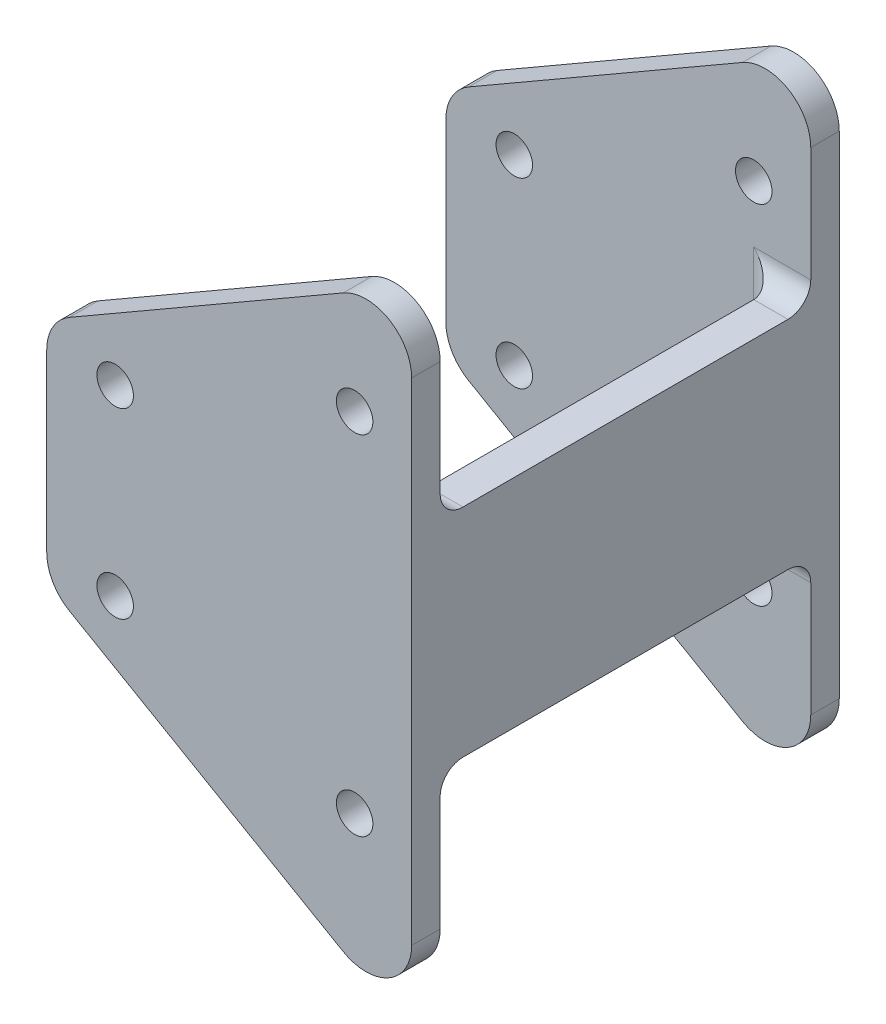
SolidWorks part; units mm, degrees
ref_plane "Front Plane" through (0, 0, 0) normal (0, 0, 1) x (1, 0, 0)
ref_plane "Top Plane" through (0, 0, 0) normal (0, 1, 0) x (1, 0, 0)
ref_plane "Right Plane" through (0, 0, 0) normal (1, 0, 0) x (0, 0, -1)
sketch "Sketch2" plane through (0, 0, 0) normal (0, 0, 1) x (1, 0, 0)
  line L2 (-32, -7.6906) -> (-32, 7.6906)
  line L4 (-30, 11.1547) -> (-6, 25.0111)
  line L5 (0, 21.547) -> (0, -21.547)
  line L6 (-6, -25.0111) -> (-30, -11.1547)
  arc A4 (-6, 25.0111) -> (0, 21.547) centre (-4, 21.547) cw
  arc A5 (0, -21.547) -> (-6, -25.0111) centre (-4, -21.547) cw
  arc A6 (-32, -7.6906) -> (-30, -11.1547) centre (-28, -7.6906) ccw
  arc A7 (-32, 7.6906) -> (-30, 11.1547) centre (-28, 7.6906) cw
  point P0 (0, 0)
  point P7 (-35, -25)
  point P9 (0, 28.4752)
  point P10 (-35, 0)
  point P13 (0, 0)
  point P14 (0, -28.4752)
  point P16 (0, -28.4752)
  point P18 (-32, -10)
  point P21 (-32, 10)
  dimension "D4" = 32
  dimension "D5" = 4
  dimension "D1" = 20
  dimension "D2" = 60
  dimension "D3" = 60
extrude "Boss-Extrude1" add sketch "Sketch2" along normal blind 2.5
sketch "Sketch3" plane through (0, 0, 2.5) normal (0, 0, 1) x (1, 0, 0)
  line L1 (0, 9.5) -> (-3, 9.5)
  line L2 (0, 9.5) -> (0, -9.5)
  line L3 (0, -9.5) -> (-3, -9.5)
  line L4 (-3, 9.5) -> (-3, -9.5)
  line L5 (0, -21.547) -> (0, 21.547) construction
  point P9 (0, 0)
  point P10 (0, 0)
  dimension "D1" = 19
  dimension "D2" = 3
extrude "Boss-Extrude2" add sketch "Sketch3" along normal blind 35
pattern_linear "LPattern1" count 2 spacing 35 along (0, 0, 1) of "Boss-Extrude1"
sketch "Sketch6" plane through (0, 0, 2.5) normal (0, 0, 1) x (1, 0, 0)
  line L2 (-32, 7.6906) -> (-32, -7.6906) construction
  circle A0 centre (-26, 8) radius 1.6
  circle A1 centre (-26, -8) radius 1.6
  dimension "D1" = 3.2
  dimension "D4" = 3.2
  dimension "D2" = 8
  dimension "D3" = 6
  dimension "D5" = 16
extrude "Cut-Extrude2" cut sketch "Sketch6" against normal blind 10 and the other way through all
sketch "Sketch8" plane through (0, 0, 37.5) normal (0, 0, 1) x (1, 0, 0)
  line L0 (0, 21.547) -> (0, -21.547) construction
  circle A0 centre (-5, 16.5111) radius 1.6
  circle A1 centre (-5, -14.0111) radius 1.6
  dimension "D1" = 3.2
  dimension "D2" = 5
  dimension "D3" = 8.5
  dimension "D4" = 2
  dimension "D5" = 11
extrude "Cut-Extrude4" cut sketch "Sketch8" against normal through all
fillet "Fillet1" radius 2 4 edges at (-1.5, -9.5, 35) (-1.5, -9.5, 2.5) (-1.5, 9.5, 2.5) (-1.5, 9.5, 35)
fillet "Fillet2" radius 2 2 edges at (-3, 0, 2.5) (-3, 0, 35)
